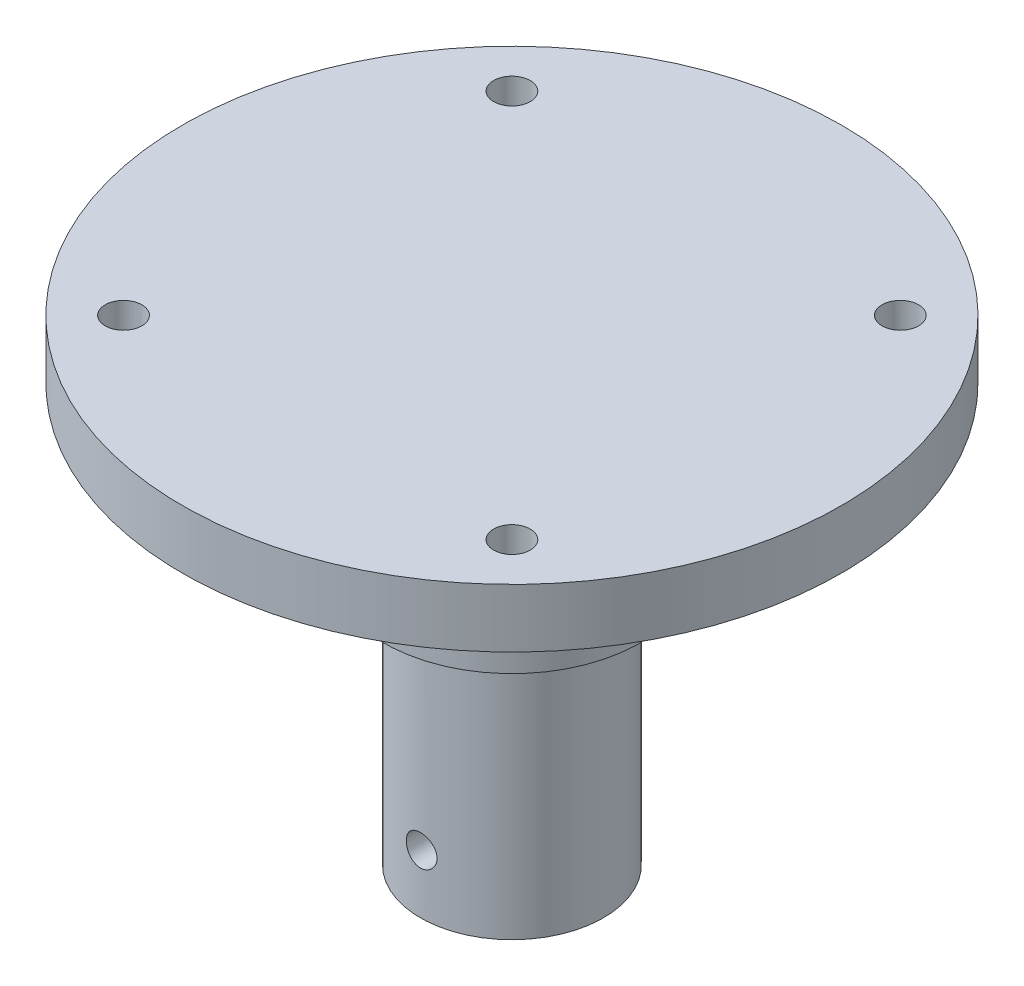
SolidWorks part; units mm, degrees
material "Liga 1060"
ref_plane "Plano frontal" through (0, 0, 0) normal (0, 0, 1) x (1, 0, 0)
ref_plane "Plano superior" through (0, 0, 0) normal (0, 1, 0) x (1, 0, 0)
ref_plane "Plano direito" through (0, 0, 0) normal (1, 0, 0) x (0, 0, -1)
sketch "Esboço1" plane through (0, 0, 0) normal (0, 0, 1) x (1, 0, 0)
  line L0 (0, 0) -> (0, 65)
  line L1 (0, 0) -> (17.5, 0)
  line L2 (17.5, 0) -> (17.5, 57)
  line L3 (17.5, 57) -> (45, 57)
  line L4 (45, 57) -> (45, 65)
  line L5 (45, 65) -> (0, 65)
  line L6 (0, 0) -> (0, 65) construction
  dimension "D1" = 65
  dimension "D2" = 17.5
  dimension "D3" = 8
  dimension "D4" = 45
revolve "Revolução1" add sketch "Esboço1" angle 360 about L0
hole_wizard "Broca de rosquear para tarraxa de M62" positions "Esboço2" profile "Esboço3" hole size "M6" standard "ISO" end condition through all
sketch "Esboço2" plane through (0, 65, 0) normal (0, 1, 0) x (1, 0, 0)
  line L1 (-26.5165, -26.5165) -> (26.5165, -26.5165)
  line L2 (-26.5165, -26.5165) -> (-26.5165, 26.5165)
  line L3 (-26.5165, 26.5165) -> (26.5165, 26.5165)
  line L4 (26.5165, -26.5165) -> (26.5165, 26.5165)
  line L5 (-26.5165, -26.5165) -> (26.5165, 26.5165) construction
  line L6 (-26.5165, 26.5165) -> (26.5165, -26.5165) construction
  point P6 (26.5165, 26.5165)
  point P97 (-26.5165, -26.5165)
  point P98 (-26.5165, 26.5165)
  point P99 (26.5165, -26.5165)
  dimension "D1" = 75
sketch "Esboço3" plane through (26.5165, 65, -26.5165) normal (1, 0, 0) x (0, 0, 1)
  line L0 (0, 0) -> (0, 65)
  line L1 (0, 65) -> (2.5, 65)
  line L2 (2.5, 65) -> (2.5, 0)
  line L5 (2.5, 0) -> (0, 0)
  line L11 (0, -6.35) -> (0, 107.95) construction
  dimension "Thru Hole Dia." = 5
  dimension "Thru Hole Depth" = 65
sketch "Esboço4" plane through (0, 0, 0) normal (0, -1, 0) x (1, 0, 0)
  circle A0 centre (0, 0) radius 3.1
  dimension "D1" = 6.2
extrude "Corte-extrusão1" cut sketch "Esboço4" against normal blind 18
hole_wizard "Broca de rosquear para tarraxa de M52" positions "Esboço6" profile "Esboço7" hole size "M5" standard "ISO"
sketch "Esboço6" plane through (0, 0, 0) normal (0, 0, 1) x (1, 0, 0)
  line L0 (-17.5, 0) -> (17.5, 0) construction
  point P0 (0, 8)
  dimension "D1" = 8
sketch "Esboço7" plane through (0, 8, 0) normal (1, 0, 0) x (0, 1, 0)
  line L0 (0, 0) -> (0, 45)
  line L1 (0, 45) -> (2.1, 45)
  line L2 (2.1, 45) -> (2.1, 0)
  line L5 (2.1, 0) -> (0, 0)
  line L11 (0, -6.35) -> (0, 107.95) construction
  dimension "Thru Hole Dia." = 4.2
  dimension "Thru Hole Depth" = 45
sketch "Esboço8" plane through (0, 0, 0) normal (0, -1, 0) x (1, 0, 0)
  circle A0 centre (0, 0) radius 12.5
  circle A1 centre (0, 0) radius 17.5 construction
  circle A2 centre (0, 0) radius 17.5
  dimension "D1" = 25
extrude "Corte-extrusão2" cut sketch "Esboço8" against normal blind 35
